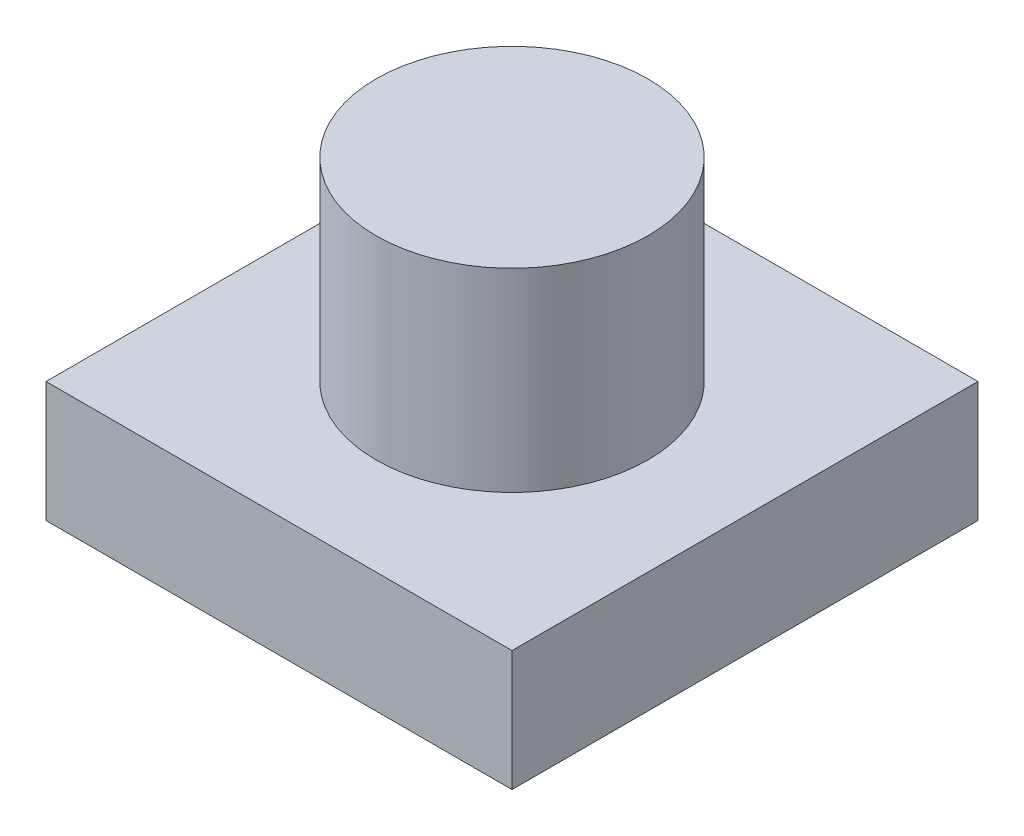
SolidWorks part; units mm, degrees
ref_plane "前视" through (0, 0, 0) normal (0, 0, 1) x (1, 0, 0)
ref_plane "上视" through (0, 0, 0) normal (0, 1, 0) x (1, 0, 0)
ref_plane "右视" through (0, 0, 0) normal (1, 0, 0) x (0, 0, -1)
sketch "草图1" plane through (0, 0, 0) normal (0, 1, 0) x (1, 0, 0)
  line L0 (0, 96.9306) -> (0, -101.3275) construction
  line L1 (-119.7143, 0) -> (134.9034, 0) construction
  line L3 (-6, 6) -> (6, 6)
  line L4 (-6, 6) -> (-6, -6)
  line L5 (-6, -6) -> (6, -6)
  line L6 (6, 6) -> (6, -6)
  dimension "D1" = 12
  dimension "D2" = 12
extrude "拉伸1" add sketch "草图1" along normal blind 3.1
sketch "草图2" plane through (0, 3.1, 0) normal (0, 1, 0) x (-1, 0, 0)
  line L0 (-6, 0) -> (8.7109, 0) construction
  line L1 (-6, 6) -> (-6, -6) construction
  line L2 (0, -7.8518) -> (0, 10.0992) construction
  circle A0 centre (0, 0) radius 3.5
  dimension "D1" = 7
extrude "拉伸2" add sketch "草图2" along normal blind 5
sketch "草图3" plane through (-6, 0, 0) normal (-1, 0, 0) x (0, 0, 1)
  line L0 (0, -6.9925) -> (0, 14.8526) construction
sketch "草图4" plane through (0, 8.1, 0) normal (0, 1, 0) x (-1, 0, 0)
  line L0 (0, -4.1469) -> (0, 4.9476) construction
  line L1 (-3.9082, 0) -> (5.1305, 0) construction
sketch "草图5" plane through (0, 0, 0) normal (0, -1, 0) x (1, 0, 0)
  line L0 (10.1949, 0) -> (-13.2034, 0) construction
  line L1 (0, 8.665) -> (0, -9.2576) construction
